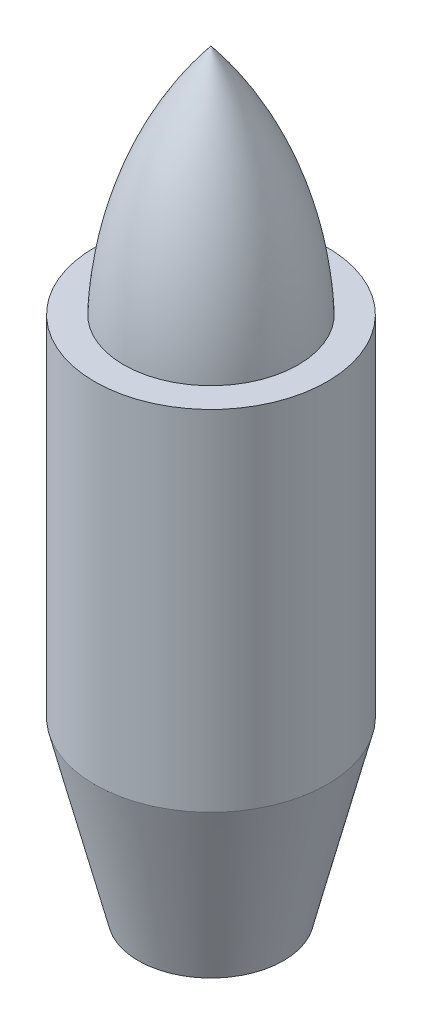
SolidWorks part; units mm, degrees
ref_plane "Front Plane" through (0, 0, 0) normal (0, 0, 1) x (1, 0, 0)
ref_plane "Top Plane" through (0, 0, 0) normal (0, 1, 0) x (1, 0, 0)
ref_plane "Right Plane" through (0, 0, 0) normal (1, 0, 0) x (0, 0, -1)
sketch "Sketch1" plane through (0, 0, 0) normal (0, 1, 0) x (1, 0, 0)
  circle A0 centre (0, 0) radius 200
  dimension "D1" = 400
extrude "Boss-Extrude1" add sketch "Sketch1" along normal blind 600
ref_plane "Plane1" through (0, -300, 0) normal (0, -1, 0) x (-1, 0, 0)
sketch "Sketch2" plane through (0, -300, 0) normal (0, -1, 0) x (-1, 0, 0)
  circle A0 centre (0, 0) radius 125
  dimension "D1" = 250
loft "Loft1" add profiles "Sketch2" section "Sketch2" section edge at (0, 0, 200)
sketch "Sketch3" plane through (0, 0, 0) normal (1, 0, 0) x (0, 0, -1)
  line L0 (0, 1000) -> (0, 600)
  line L1 (200, 600) -> (-200, 600) construction
  arc A0 (-150, 600) -> (0, 1000) centre (527.784, 573.956) cw
  dimension "D1" = 400
revolve "Revolve-Thin1" add sketch "Sketch3" angle 360 about L0
